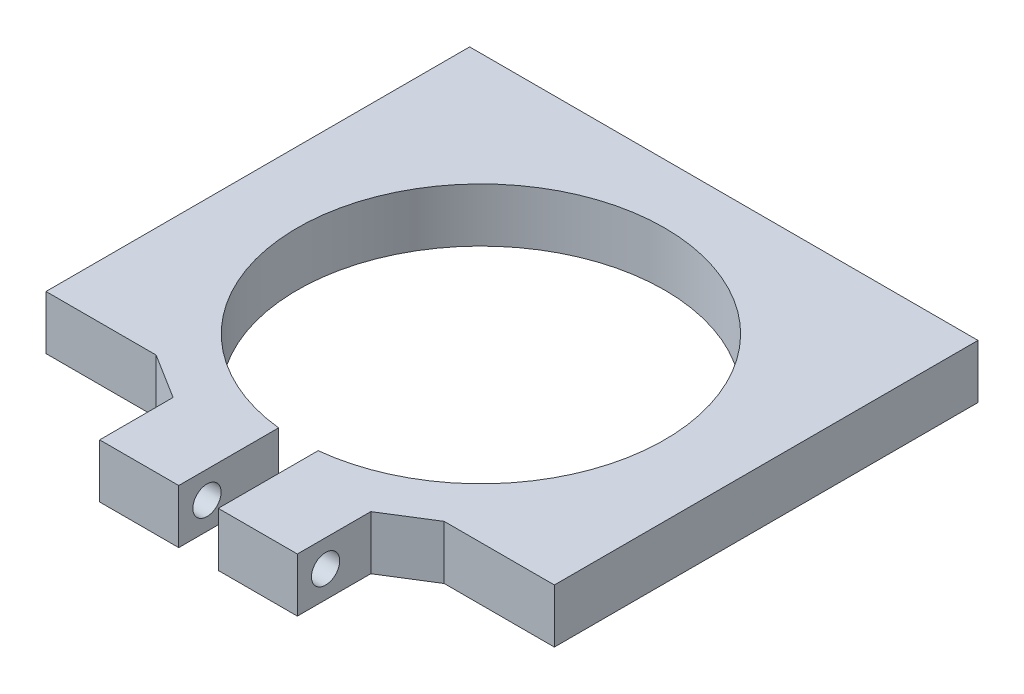
SolidWorks part; units mm, degrees
ref_plane "Plano frontal" through (0, 0, 0) normal (0, 0, 1) x (1, 0, 0)
ref_plane "Plano superior" through (0, 0, 0) normal (0, 1, 0) x (1, 0, 0)
ref_plane "Plano direito" through (0, 0, 0) normal (1, 0, 0) x (0, 0, -1)
sketch "Esboço1" plane through (0, 0, 0) normal (0, 1, 0) x (1, 0, 0)
  line L0 (45, 46.5) -> (-45, -46.5) construction
  line L1 (-45, 46.5) -> (45, 46.5)
  line L2 (-45, 46.5) -> (-45, -46.5)
  line L3 (-45, -46.5) -> (45, -46.5)
  line L4 (45, 46.5) -> (45, -46.5)
  dimension "D1" = 90
  dimension "D2" = 93
extrude "Ressalto-extrusão1" add sketch "Esboço1" along normal blind 9.53 contours L2 L3 L4 L1
sketch "Esboço3" plane through (0, 9.53, 0) normal (0, 1, 0) x (1, 0, 0)
  line L0 (-45, -46.5) -> (45, -46.5) construction
  line L1 (45, 46.5) -> (45, -46.5) construction
  circle A0 centre (0, 3.5) radius 32.51
  dimension "D1" = 65.02
  dimension "D2" = 50
  dimension "D3" = 45
extrude "Corte-extrusão2" cut sketch "Esboço3" against normal through all
sketch "Esboço2" plane through (0, 0, -46.5) normal (0, 0, -1) x (-1, 0, 0)
  line L0 (45, 4.765) -> (-45, 4.765) construction
  line L1 (45, 9.53) -> (45, 0) construction
  line L2 (-45, 9.53) -> (-45, 0) construction
  circle A0 centre (-40, 4.765) radius 2
  circle A1 centre (-25, 4.765) radius 2
  circle A2 centre (25, 4.765) radius 2
  circle A3 centre (40, 4.765) radius 2
  dimension "D5" = 4
  dimension "D6" = 4
  dimension "D7" = 4
  dimension "D8" = 4
  dimension "D1" = 5
  dimension "D2" = 20
  dimension "D3" = 5
  dimension "D4" = 20
extrude "Corte-extrusão1" cut sketch "Esboço2" against normal blind 19
sketch "Esboço5" plane through (0, 9.53, 0) normal (0, 1, 0) x (1, 0, 0)
  line L0 (0, -46.5) -> (0, -37.4552) construction
  line L1 (45, -46.5) -> (17.5, -46.5)
  line L2 (45, -46.5) -> (45, -33.5)
  line L3 (45, -33.5) -> (17.5, -33.5)
  line L4 (17.5, -46.5) -> (17.5, -33.5)
  line L5 (-45, -46.5) -> (-17.5, -46.5)
  line L6 (-45, -46.5) -> (-45, -33.5)
  line L7 (-45, -33.5) -> (-17.5, -33.5)
  line L8 (-17.5, -46.5) -> (-17.5, -33.5)
  line L9 (-45, -46.5) -> (45, -46.5) construction
  dimension "D1" = 17.5
  dimension "D2" = 17.5
  dimension "D3" = 13
  dimension "D4" = 13
extrude "Corte-extrusão4" cut sketch "Esboço5" against normal up to next
sketch "Esboço6" plane through (0, 9.53, 0) normal (0, 1, 0) x (1, 0, 0)
  line L1 (0, 0) -> (0, -46.5) construction
  line L2 (-17.5, -46.5) -> (17.5, -46.5) construction
  line L4 (3.5, -46.5) -> (-3.5, -46.5)
  line L5 (3.5, -46.5) -> (3.5, -20.1703)
  line L6 (3.5, -20.1703) -> (-3.5, -20.1703)
  line L7 (-3.5, -46.5) -> (-3.5, -20.1703)
  dimension "D1" = 3.5
  dimension "D2" = 3.5
extrude "Corte-extrusão5" cut sketch "Esboço6" against normal up to next
sketch "Esboço7" plane through (-17.5, 0, 0) normal (-1, 0, 0) x (0, 0, 1)
  line L0 (46.5, 9.53) -> (36.5, 0) construction
  line L1 (46.5, 0) -> (33.5, 0) construction
  circle A0 centre (41.5, 4.765) radius 2.5
  dimension "D2" = 5
  dimension "D1" = 10
extrude "Corte-extrusão6" cut sketch "Esboço7" against normal up to surface (35 mm away) up to face at (17.5, 4.765, 40)
sketch "Esboço9" plane through (0, 9.53, 0) normal (0, 1, 0) x (-1, 0, 0)
  line L0 (0, 0) -> (0, 41.0123) construction
  line L1 (45, -46.5) -> (45, 33.5) construction
  line L2 (45, 28.5) -> (25.5, 28.5)
  line L3 (45, 28.5) -> (45, 33.5)
  line L4 (45, 33.5) -> (17.5, 33.5)
  line L5 (-25.5, 28.5) -> (-17.5, 33.5)
  line L9 (-45, 33.5) -> (-17.5, 33.5)
  line L10 (-45, 28.5) -> (-45, 33.5)
  line L11 (-45, 28.5) -> (-25.5, 28.5)
  line L13 (17.5, 46.5) -> (3.5, 46.5) construction
  line L14 (25.5, 28.5) -> (17.5, 33.5)
  dimension "D2" = 18
extrude "Corte-extrusão8" cut sketch "Esboço9" against normal through all
